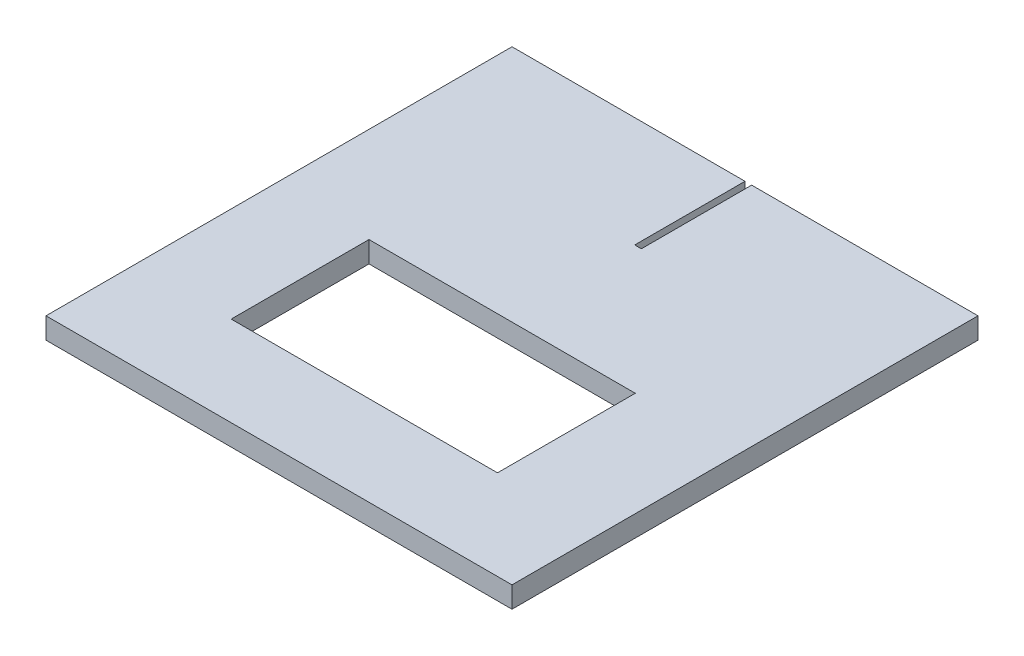
SolidWorks part; units mm, degrees
ref_plane "Front Plane" through (0, 0, 0) normal (0, 0, 1) x (1, 0, 0)
ref_plane "Top Plane" through (0, 0, 0) normal (0, 1, 0) x (1, 0, 0)
ref_plane "Right Plane" through (0, 0, 0) normal (1, 0, 0) x (0, 0, -1)
sketch "Sketch1" plane through (0, 0, 0) normal (0, 1, 0) x (1, 0, 0)
  line L1 (-35, -35) -> (35, -35)
  line L2 (-35, -35) -> (-35, 35)
  line L3 (-35, 35) -> (35, 35)
  line L4 (35, -35) -> (35, 35)
  line L5 (-35, -35) -> (35, 35) construction
  line L6 (-35, 35) -> (35, -35) construction
  point P1 (0, 0)
  dimension "D1" = 70
  dimension "D2" = 70
extrude "Boss-Extrude1" add sketch "Sketch1" along normal blind 3.175
sketch "Sketch2" plane through (0, 3.175, 0) normal (0, 1, 0) x (1, 0, 0)
  line L0 (35, 35) -> (-35, 35) construction
  line L1 (0, 35) -> (1, 35)
  line L2 (0, 35) -> (0, 18.4363)
  line L3 (0, 18.4363) -> (1, 18.4363)
  line L4 (1, 35) -> (1, 18.4363)
  dimension "D1" = 1
extrude "Cut-Extrude1" cut sketch "Sketch2" against normal blind 3.175
sketch "Sketch3" plane through (0, 0, 0) normal (0, -1, 0) x (-1, 0, 0)
  line L1 (-19.3374, -0.8181) -> (20.6626, -0.8181)
  line L2 (-19.3374, -0.8181) -> (-19.3374, -21.5181)
  line L3 (-19.3374, -21.5181) -> (20.6626, -21.5181)
  line L4 (20.6626, -0.8181) -> (20.6626, -21.5181)
  dimension "D1" = 20.7
  dimension "D2" = 40
extrude "Cut-Extrude2" cut sketch "Sketch3" against normal blind 3.175 contours L3 L4 L1 L2
